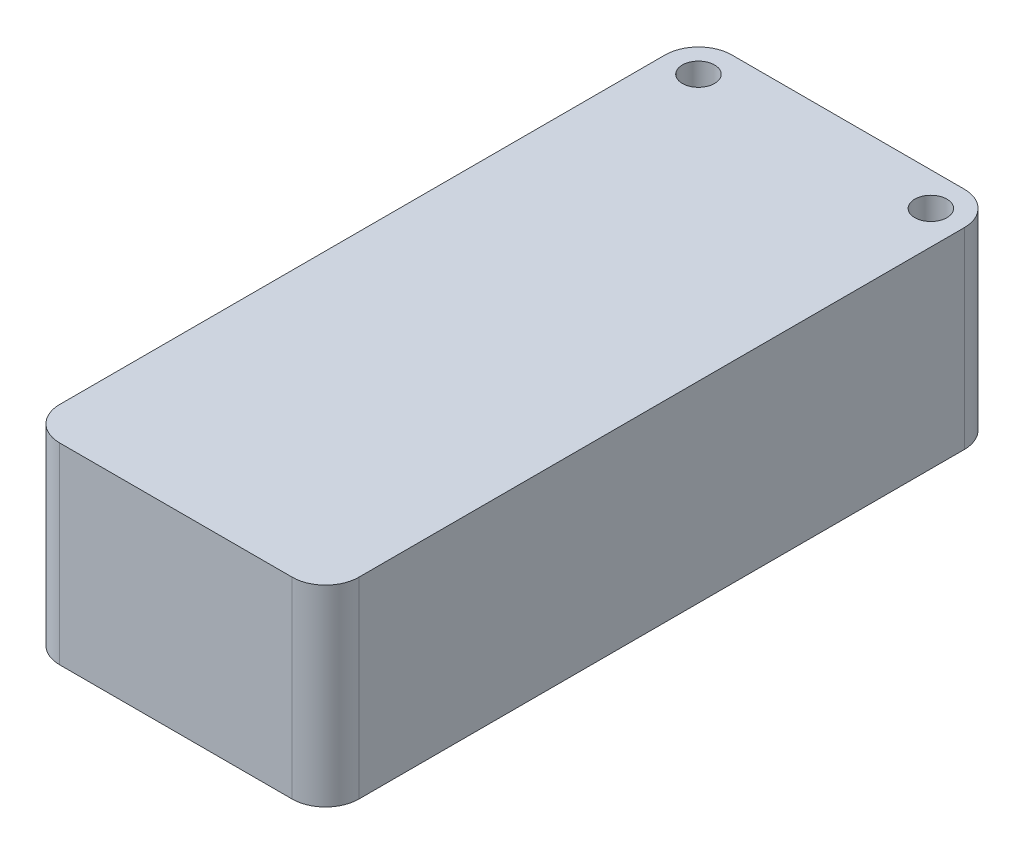
SolidWorks part; units mm, degrees
ref_plane "Front Plane" through (0, 0, 0) normal (0, 0, 1) x (1, 0, 0)
ref_plane "Top Plane" through (0, 0, 0) normal (0, 1, 0) x (1, 0, 0)
ref_plane "Right Plane" through (0, 0, 0) normal (1, 0, 0) x (0, 0, -1)
sketch "Sketch1" plane through (0, 0, 0) normal (0, 1, 0) x (1, 0, 0)
  line L1 (0, 0) -> (22.76, 0)
  line L2 (0, 0) -> (0, -51.13)
  line L3 (0, -51.13) -> (22.76, -51.13)
  line L4 (22.76, 0) -> (22.76, -51.13)
  line L5 (0, 0) -> (22.76, -51.13) construction
  line L6 (0, -51.13) -> (22.76, 0) construction
  point P4 (11.38, -25.565)
  dimension "D1" = 51.13
  dimension "D2" = 22.76
extrude "Boss-Extrude1" add sketch "Sketch1" along normal blind 14.62
sketch "Sketch2" plane through (0, 14.62, 0) normal (0, 1, 0) x (1, 0, 0)
  line L0 (22.76, 0) -> (0, 0) construction
  line L1 (0, 0) -> (0, -51.13) construction
  line L2 (22.76, -51.13) -> (22.76, 0) construction
  circle A0 centre (2.54, -2.54) radius 1.225
  circle A1 centre (20.22, -2.54) radius 1.225
  dimension "D1" = 2.54
  dimension "D2" = 2.54
  dimension "D3" = 2.54
  dimension "D4" = 2.54
  dimension "D5" = 2.45
  dimension "D6" = 2.45
extrude "Cut-Extrude1" cut sketch "Sketch2" against normal through all both and the other way through all
fillet "Fillet1" radius 2.54 4 edges at (22.76, 7.31, 51.13) (0, 7.31, 51.13) (0, 7.31, 0) (22.76, 7.31, 0)
sketch "Sketch4" plane through (0, 0, 0) normal (0, 0, -1) x (-1, 0, 0)
  line L0 (-11.38, 14.62) -> (-11.38, 0) construction
  line L1 (-20.22, 14.62) -> (-2.54, 14.62) construction
  line L2 (-20.22, 0) -> (-2.54, 0) construction
  line L4 (-15.88, 11.79) -> (-6.88, 11.79)
  line L5 (-15.88, 11.79) -> (-15.88, 8.59)
  line L6 (-15.88, 8.59) -> (-6.88, 8.59)
  line L7 (-6.88, 11.79) -> (-6.88, 8.59)
  line L8 (-15.88, 11.79) -> (-6.88, 8.59) construction
  line L9 (-15.88, 8.59) -> (-6.88, 11.79) construction
  point P10 (-11.38, 10.19)
  point P11 (0, 0)
  point P12 (-11.38, 8.6912)
  dimension "D1" = 9
  dimension "D2" = 3.2
  dimension "D3" = 8.59
extrude "Boss-Extrude3" add sketch "Sketch4" along normal blind 1.12
